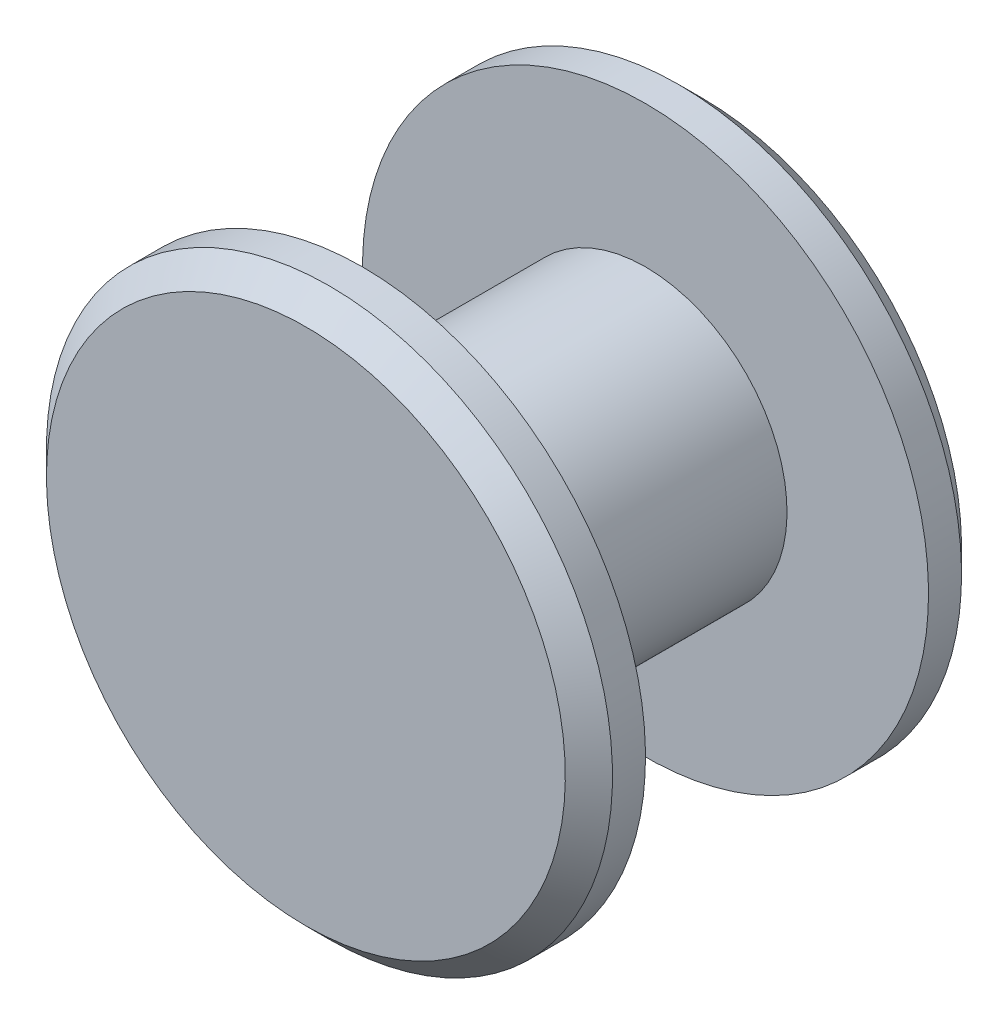
SolidWorks part; units mm, degrees
ref_plane "Front Plane" through (0, 0, 0) normal (0, 0, 1) x (1, 0, 0)
ref_plane "Top Plane" through (0, 0, 0) normal (0, 1, 0) x (1, 0, 0)
ref_plane "Right Plane" through (0, 0, 0) normal (1, 0, 0) x (0, 0, -1)
sketch "Sketch1" plane through (0, 0, 0) normal (1, 0, 0) x (0, 0, -1)
  line L0 (0, 0) -> (0, 3)
  line L1 (0, 3) -> (0.6, 3)
  line L2 (0.6, 3) -> (0.6, 1.5)
  line L3 (0.6, 1.5) -> (3.6, 1.5)
  line L4 (3.6, 1.5) -> (3.6, 3)
  line L5 (3.6, 3) -> (4.2, 3)
  line L6 (4.2, 3) -> (4.2, 0)
  line L7 (4.2, 0) -> (0, 0)
  line L8 (0, 0) -> (-4.2, 0) construction
  dimension "D1" = 3
  dimension "D2" = 0.6
  dimension "D3" = 3
  dimension "D4" = 6
revolve "Revolve1" add sketch "Sketch1" angle 360 about L8
chamfer "Chamfer1" distance 0.25 angle 45 2 edges at (0, 3, -4.2) (0, 3, 0)
equation "\"a\"= 1"
equation "\"b\"= 1"
equation "\"c\"= 1"
equation "\"d\"= 1"
equation "\"e\"= 1"
equation "\"x\"= 1"
equation "\"y\"= 1"
equation "\"z\"= 1"
